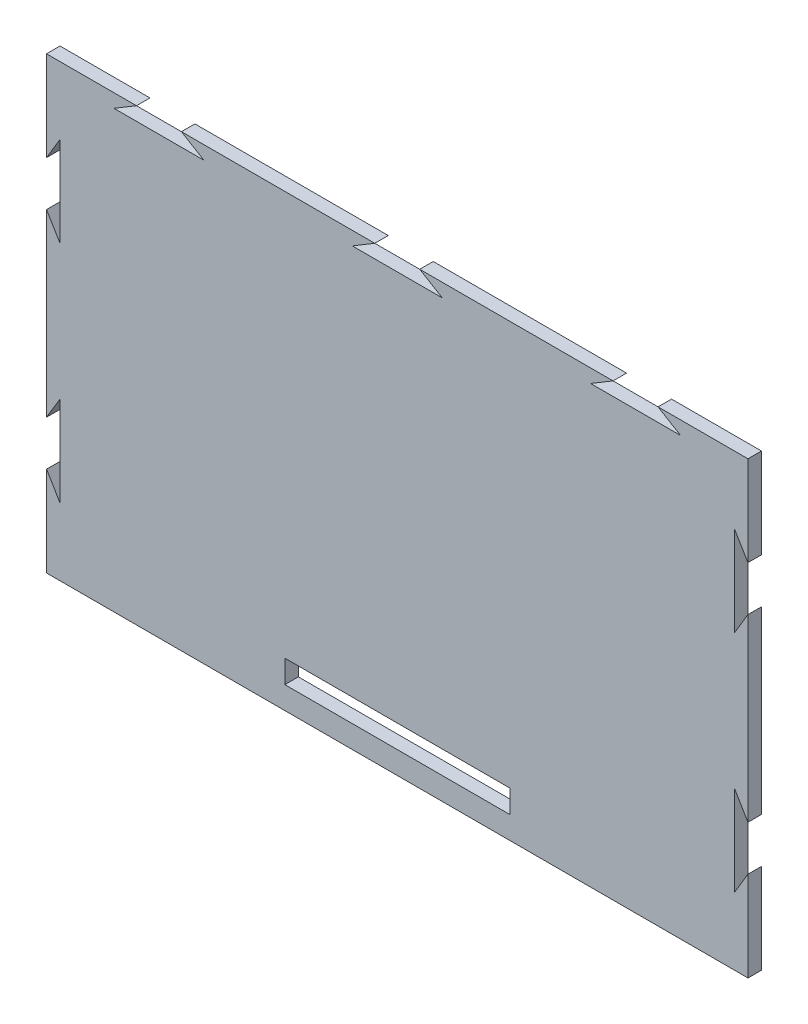
SolidWorks part; units mm, degrees
ref_plane "Plan de face" through (0, 0, 0) normal (0, 0, 1) x (1, 0, 0)
ref_plane "Plan de dessus" through (0, 0, 0) normal (0, 1, 0) x (1, 0, 0)
ref_plane "Plan de droite" through (0, 0, 0) normal (1, 0, 0) x (0, 0, -1)
sketch "Esquisse1" plane through (0, 0, 0) normal (0, 0, 1) x (1, 0, 0)
  line L1 (-78, -50) -> (78, -50)
  line L2 (-78, -50) -> (-78, 50)
  line L3 (-78, 50) -> (78, 50)
  line L4 (78, -50) -> (78, 50)
  point P0 (0, 0)
  dimension "D1" = 156
  dimension "D2" = 100
extrude "Boss.-Extru.1" add sketch "Esquisse1" along normal blind 3
sketch "Esquisse2" plane through (0, 0, 0) normal (0, 0, -1) x (-1, 0, 0)
  line L0 (-58, 50) -> (-63, 47)
  line L1 (-78, 50) -> (78, 50) construction
  line L2 (-63, 47) -> (-43, 47)
  line L3 (-43, 47) -> (-48, 50)
  line L4 (-10, 47) -> (-5, 50)
  line L5 (-5, 50) -> (5, 50)
  line L6 (5, 50) -> (10, 47)
  line L7 (10, 47) -> (-10, 47)
  line L8 (-58, 50) -> (-48, 50)
  line L9 (48, 50) -> (43, 47)
  line L10 (43, 47) -> (63, 47)
  line L11 (63, 47) -> (58, 50)
  line L12 (58, 50) -> (48, 50)
  point P13 (0, 0)
  point P16 (0, 0)
  point P17 (86.6044, 50.582)
  dimension "D1" = 10
  dimension "D2" = 10
  dimension "D3" = 20
  dimension "D4" = 5
  dimension "D5" = 3
  dimension "D6" = 3
  dimension "D7" = 20
  dimension "D8" = 5
  dimension "D9" = 20
  dimension "D10" = 43
  dimension "D11" = 3
  dimension "D12" = 20
  dimension "D13" = 10
  dimension "D14" = 5
  dimension "D15" = 20
extrude "Enlèv. mat.-Extru.1" cut sketch "Esquisse2" against normal blind 3
sketch "Esquisse4" plane through (0, 0, 0) normal (0, 0, -1) x (-1, 0, 0)
  line L0 (-78, 30) -> (-75, 35)
  line L1 (-78, -50) -> (-78, 50) construction
  line L2 (-75, 35) -> (-75, 15)
  line L3 (-75, 15) -> (-78, 20)
  line L4 (-78, 30) -> (-78, 20)
  line L5 (-78, -20) -> (-75, -15)
  line L6 (-75, -15) -> (-75, -35)
  line L7 (-75, -35) -> (-78, -30)
  line L8 (-78, -20) -> (-78, -30)
  dimension "D1" = 20
  dimension "D2" = 3
  dimension "D3" = 10
  dimension "D4" = 5
  dimension "D5" = 20
  dimension "D6" = 20
  dimension "D7" = 5
  dimension "D8" = 10
  dimension "D9" = 3
  dimension "D10" = 40
extrude "Enlèv. mat.-Extru.3" cut sketch "Esquisse4" against normal blind 3
sketch "Esquisse5" plane through (0, 0, 0) normal (0, 0, -1) x (-1, 0, 0)
  line L0 (78, 30) -> (75, 35)
  line L1 (78, 50) -> (78, -50) construction
  line L2 (75, 35) -> (75, 15)
  line L3 (75, 15) -> (78, 20)
  line L4 (78, -20) -> (75, -15)
  line L5 (75, -15) -> (75, -35)
  line L6 (75, -35) -> (78, -30)
  line L7 (78, 30) -> (78, 20)
  line L8 (78, -20) -> (78, -30)
  dimension "D1" = 20
  dimension "D2" = 20
  dimension "D3" = 10
  dimension "D4" = 10
  dimension "D5" = 5
  dimension "D6" = 5
  dimension "D7" = 3
  dimension "D8" = 3
  dimension "D9" = 20
  dimension "D10" = 40
extrude "Enlèv. mat.-Extru.4" cut sketch "Esquisse5" against normal blind 3
sketch "Esquisse6" plane through (0, 0, 0) normal (0, 0, -1) x (-1, 0, 0)
  line L0 (-78, -50) -> (-78, -30) construction
  line L1 (-25.1, -39.9) -> (25, -39.9)
  line L2 (-25.1, -39.9) -> (-25.1, -45)
  line L3 (-25.1, -45) -> (25, -45)
  line L4 (25, -39.9) -> (25, -45)
  line L8 (78, -50) -> (-78, -50) construction
  point P0 (-19.9799, -34.8359)
  dimension "D1" = 50.1
  dimension "D2" = 52.9
  dimension "D3" = 5.1
  dimension "D4" = 5
extrude "Enlèv. mat.-Extru.5" cut sketch "Esquisse6" against normal blind 3
